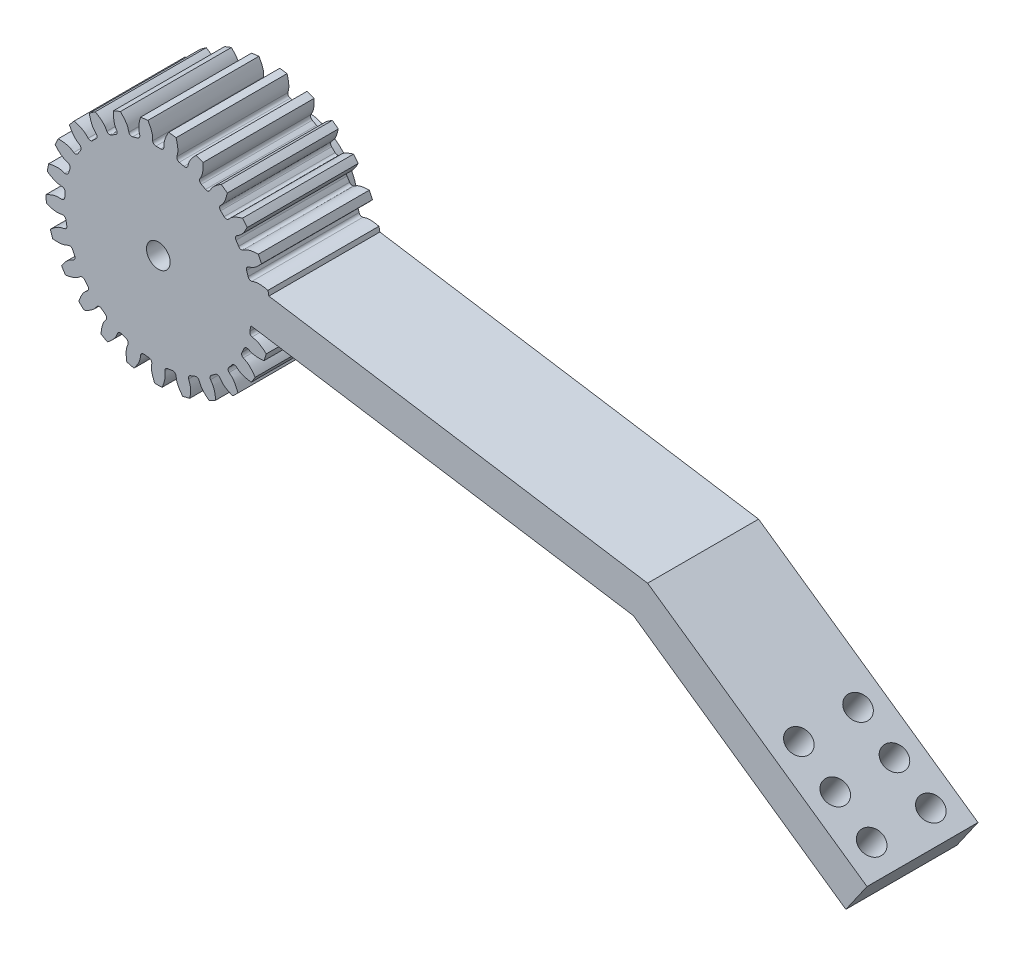
SolidWorks part; units mm, degrees
ref_plane "Front Plane" through (0, 0, 0) normal (0, 0, 1) x (1, 0, 0)
ref_plane "Top Plane" through (0, 0, 0) normal (0, 1, 0) x (1, 0, 0)
ref_plane "Right Plane" through (0, 0, 0) normal (1, 0, 0) x (0, 0, -1)
ref_axis "Axis1" through (0, 0, -88.99) along (0, 0, 1)
sketch "草图1" plane through (0, 0, 0) normal (0, 0, 1) x (1, 0, 0)
  circle A0 centre (0, 0) radius 15.1875
extrude "LaShenA" add sketch "草图1" along normal blind 15
sketch "SketchA" plane through (0, 0, 15) normal (0, 0, 1) x (1, 0, 0)
  line L0 (0, 0) -> (0, 15.1875) construction
  arc A0 (0.3244, 12.6521) -> (-0.3244, 12.6521) centre (0, 0) ccw
  arc A1 (1.842, 15.7559) -> (-1.842, 15.7559) centre (0, 0) ccw
  arc A2 (-0.3244, 12.6521) -> (-0.7617, 13.0474) centre (-0.3354, 13.0795) cw
  arc A3 (0.7617, 13.0474) -> (0.3244, 12.6521) centre (0.3354, 13.0795) cw
  circle A4 centre (0, 0) radius 13.6146 construction
  circle A5 centre (0, 0) radius 15.1875 construction
  circle A6 centre (0, 0) radius 12.6562 construction
  circle A7 centre (0, 0) radius 14.0625 construction
  spline S0 degree 3 poles (0.7617, 13.0474) (0.7753, 13.2289) (0.7594, 13.4417) (0.7888, 13.6649) (0.7997, 13.7227) (0.8093, 13.7685) (0.8217, 13.8211) (0.837, 13.8804) (0.8557, 13.9462) (0.878, 14.0185) (0.9042, 14.097) (0.9347, 14.1818) (0.9697, 14.2725) (1.0095, 14.369) (1.0545, 14.4712) (1.1048, 14.5789) (1.1608, 14.6918) (1.2227, 14.8098) (1.2907, 14.9327) (1.3653, 15.0601) (1.4465, 15.192) (1.5346, 15.328) (1.6644, 15.5184) (1.7689, 15.6607) (1.842, 15.7559) knots 0.123706 0.123706 0.123706 0.123706 0.284027 0.310496 0.322147 0.335916 0.351803 0.369808 0.389932 0.412174 0.436535 0.463013 0.49161 0.522325 0.555159 0.590111 0.627181 0.666369 0.707676 0.751101 0.796644 0.844306 0.894085 1 1 1 1
  spline S1 degree 3 poles (-0.7617, 13.0474) (-0.7753, 13.2289) (-0.7594, 13.4417) (-0.7888, 13.6649) (-0.7997, 13.7227) (-0.8093, 13.7685) (-0.8217, 13.8211) (-0.837, 13.8804) (-0.8557, 13.9462) (-0.878, 14.0185) (-0.9042, 14.097) (-0.9347, 14.1818) (-0.9697, 14.2725) (-1.0095, 14.369) (-1.0545, 14.4712) (-1.1048, 14.5789) (-1.1608, 14.6918) (-1.2227, 14.8098) (-1.2907, 14.9327) (-1.3653, 15.0601) (-1.4465, 15.192) (-1.5346, 15.328) (-1.6644, 15.5184) (-1.7689, 15.6607) (-1.842, 15.7559) knots 0.123706 0.123706 0.123706 0.123706 0.284027 0.310496 0.322147 0.335916 0.351803 0.369808 0.389932 0.412174 0.436535 0.463013 0.49161 0.522325 0.555159 0.590111 0.627181 0.666369 0.707676 0.751101 0.796644 0.844306 0.894085 1 1 1 1
  dimension "D1" = 0.4275
  dimension "Db" = 27.2292
  dimension "Da" = 30.375
  dimension "Df" = 25.3125
  dimension "Dn" = 28.125
extrude "Cut-ExtrudeA" cut sketch "SketchA" against normal blind 15
pattern_circular "www.KYTool.cn" count 25 over 360 about axis through (0, 0, -88.99) along (0, 0, 1) of "Cut-ExtrudeA"
sketch "草图2" plane through (0, 0, 15) normal (0, 0, 1) x (1, 0, 0)
  circle A0 centre (0, 0) radius 1.6
  dimension "D1" = 3.2
extrude "切除-拉伸1" cut sketch "草图2" against normal through all
sketch "草图3" plane through (0, 0, 0) normal (0, 0, -1) x (-1, 0, 0)
  circle A3 centre (0, 0) radius 1.6
  circle A4 centre (0, 0) radius 7.5
  dimension "D1" = 15
  dimension "D2" = 3.2
extrude "凸台-拉伸1" add sketch "草图3" along normal blind 4.5
sketch "草图5" plane through (0, 0, 15) normal (0, 0, 1) x (1, 0, 0)
  line L1 (1.7407, -0.8828) -> (36.3404, -18.4294) construction
  line L7 (0, 0) -> (64.219, -10.0461) construction
  line L8 (1.482, -0.2318) -> (64.219, -10.0461)
  line L9 (64.219, -10.0461) -> (92.9274, -30.0667)
  line L10 (0.7728, 4.9399) -> (66.1322, -5.2846)
  line L11 (66.1322, -5.2846) -> (95.7875, -25.9655)
  line L12 (0.7728, 4.9399) -> (0.2318, 1.482)
  line L13 (92.9274, -30.0667) -> (95.7875, -25.9655)
  arc A0 (1.482, -0.2318) -> (0.2318, 1.482) centre (0, 0) ccw
  dimension "D1" = 65
  dimension "D2" = 18
  dimension "D3" = 35
  dimension "D5" = 8
  dimension "D4" = 5
extrude "凸台-拉伸3" add sketch "草图5" against normal up to surface (15 mm away) up to face at (0, 0, 0)
sketch "草图6" plane through (0, 0, 15) normal (0, 0, 1) x (1, 0, 0)
  circle A0 centre (0, 0) radius 1.6
  dimension "D1" = 3.2
extrude "切除-拉伸2" cut sketch "草图6" against normal blind 24
sketch "草图7" plane through (19.1592, 27.4733, 0) normal (0.572, 0.8202, 0) x (0.8202, -0.572, 0)
  line L0 (93.4216, -7.5) -> (89.6373, -7.5) construction
  line L1 (93.4216, 0) -> (93.4216, -15) construction
  line L2 (87.4216, -7.5) -> (83.6373, -7.5) construction
  line L3 (81.4216, -7.5) -> (77.6373, -7.5) construction
  circle A0 centre (89.9216, -11.5) radius 1.6
  circle A1 centre (89.9216, -3.5) radius 1.6
  circle A2 centre (83.9216, -11.5) radius 1.6
  circle A3 centre (83.9216, -3.5) radius 1.6
  circle A4 centre (77.9216, -11.5) radius 1.6
  circle A5 centre (77.9216, -3.5) radius 1.6
  dimension "D1" = 3.2
  dimension "D2" = 3.5
  dimension "D3" = 4
  dimension "D5" = 6
  dimension "D4" = 3
extrude "切除-拉伸3" cut sketch "草图7" against normal blind 16
